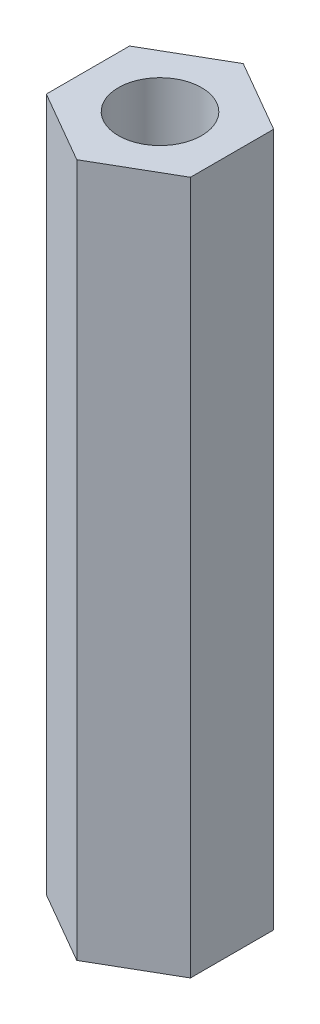
SolidWorks part; units mm, degrees
ref_plane "Front Plane" through (0, 0, 0) normal (0, 0, 1) x (1, 0, 0)
ref_plane "Top Plane" through (0, 0, 0) normal (0, 1, 0) x (1, 0, 0)
ref_plane "Right Plane" through (0, 0, 0) normal (1, 0, 0) x (0, 0, -1)
sketch "Sketch1" plane through (0, 0, 0) normal (0, 1, 0) x (1, 0, 0)
  line L0 (0, -3) -> (0, 3) construction
  line L1 (-2.5981, -1.5) -> (2.5981, 1.5) construction
  line L2 (2.5981, -1.5) -> (-2.5981, 1.5) construction
  line L3 (0, 3) -> (-2.5981, 1.5)
  line L4 (-2.5981, 1.5) -> (-2.5981, -1.5)
  line L5 (-2.5981, -1.5) -> (0, -3)
  line L6 (0, -3) -> (2.5981, -1.5)
  line L7 (2.5981, -1.5) -> (2.5981, 1.5)
  line L8 (2.5981, 1.5) -> (0, 3)
  circle A0 centre (0, 0) radius 1.5
  circle A1 centre (0, 0) radius 3 construction
  point P7 (0, 0)
  point P10 (0, 0)
  point P13 (0, 0)
extrude "Boss-Extrude1" add sketch "Sketch1" along normal blind 25
